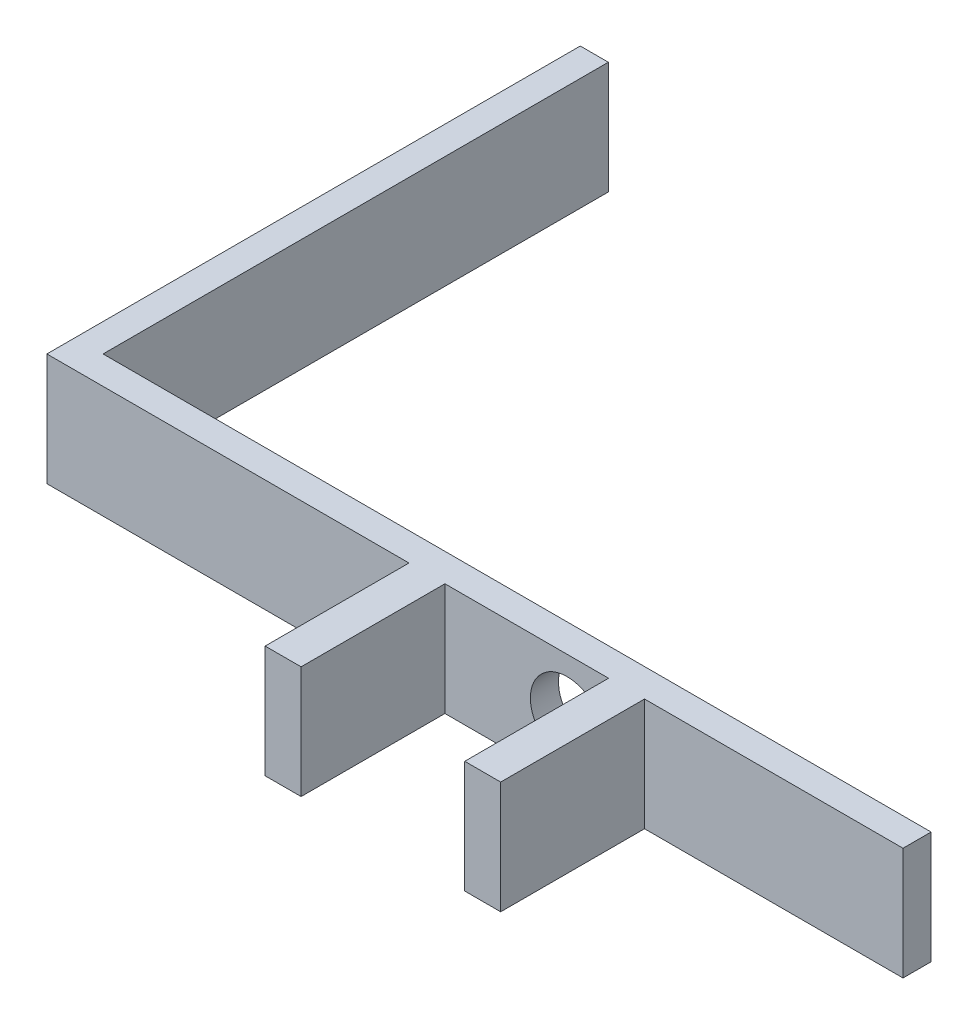
SolidWorks part; units mm, degrees
ref_plane "Front Plane" through (0, 0, 0) normal (0, 0, 1) x (1, 0, 0)
ref_plane "Top Plane" through (0, 0, 0) normal (0, 1, 0) x (1, 0, 0)
ref_plane "Right Plane" through (0, 0, 0) normal (1, 0, 0) x (0, 0, -1)
sketch "Sketch1" plane through (0, 0, 0) normal (0, 1, 0) x (1, 0, 0)
  line L1 (0, 0) -> (3.9688, 0)
  line L2 (0, 0) -> (0, 75.3427)
  line L3 (0, 75.3427) -> (3.9688, 75.3427)
  line L4 (3.9688, 3.9688) -> (3.9688, 75.3427)
  line L5 (3.9688, 0) -> (120.9358, 0)
  line L7 (3.9688, 3.9688) -> (120.9358, 3.9688)
  line L8 (120.9358, 0) -> (120.9358, 3.9688)
  dimension "D1" = 3.9688
  dimension "D2" = 3.9688
  dimension "D3" = 71.374
  dimension "D4" = 116.967
extrude "Boss-Extrude1" add sketch "Sketch1" along normal mid plane 15.875
sketch "Sketch2" plane through (0, 0, 0) normal (0, 0, 1) x (1, 0, 0)
  line L0 (120.9358, 7.9375) -> (120.9358, -7.9375) construction
  circle A0 centre (73.5013, 0) radius 5.207
  dimension "D1" = 47.4345
  dimension "D2" = 10.414
extrude "Cut-Extrude1" cut sketch "Sketch2" against normal up to surface (3.9688 mm away) up to face at (62.4522, 0, -3.9688)
sketch "Sketch4" plane through (0, 0, 0) normal (0, 0, 1) x (1, 0, 0)
  line L0 (0, -7.9375) -> (120.9358, -7.9375) construction
  line L1 (0, 7.9375) -> (120.9358, 7.9375) construction
  line L2 (51.1493, 7.9375) -> (56.2293, 7.9375)
  line L3 (51.1493, 7.9375) -> (51.1493, -7.9375)
  line L4 (51.1493, -7.9375) -> (56.2293, -7.9375)
  line L5 (56.2293, 7.9375) -> (56.2293, -7.9375)
  line L7 (79.3433, 7.9375) -> (84.4233, 7.9375)
  line L8 (79.3433, 7.9375) -> (79.3433, -7.9375)
  line L9 (79.3433, -7.9375) -> (84.4233, -7.9375)
  line L10 (84.4233, 7.9375) -> (84.4233, -7.9375)
  circle A0 centre (73.5013, 0) radius 5.207 construction
  dimension "D4" = 5.842
  dimension "D1" = 5.08
  dimension "D2" = 5.08
  dimension "D3" = 17.272
extrude "Boss-Extrude2" add sketch "Sketch4" along normal blind 20.32
